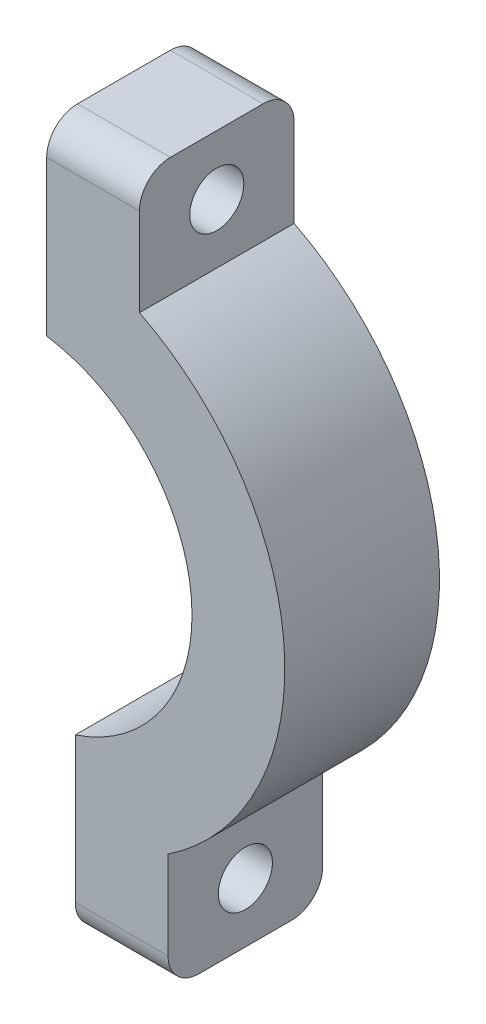
SolidWorks part; units mm, degrees
ref_plane "Front Plane" through (0, 0, 0) normal (0, 0, 1) x (1, 0, 0)
ref_plane "Top Plane" through (0, 0, 0) normal (0, 1, 0) x (1, 0, 0)
ref_plane "Right Plane" through (0, 0, 0) normal (1, 0, 0) x (0, 0, -1)
sketch "Sketch1" plane through (0, 0, 0) normal (0, 0, 1) x (1, 0, 0)
  line L2 (3.5, -17.05) -> (3.5, -10.4811)
  line L10 (3.5, -17.05) -> (3.5, -19.3581)
  line L13 (1.65, 20.4375) -> (1.65, 10.9261)
  line L16 (0, 0) -> (0, 22.7138) construction
  line L17 (7.65, 15.2375) -> (7.65, 22.9375)
  line L19 (7.65, 22.9375) -> (1.65, 22.9375)
  line L20 (1.65, 22.9375) -> (1.65, 20.4375)
  line L21 (9.5, -14.1581) -> (9.5, -21.8581)
  line L22 (9.5, -21.8581) -> (3.5, -21.8581)
  line L23 (3.5, -21.8581) -> (3.5, -19.3581)
  arc A0 (3.5, -10.4811) -> (1.65, 10.9261) centre (0, 0) ccw
  arc A1 (9.5, -14.1581) -> (7.65, 15.2375) centre (0, 0) ccw
  point P7 (0, -17.05)
  point P16 (0, 17.05)
extrude "Boss-Extrude1" add sketch "Sketch1" along normal blind 10 contours L2 A0 L13 L20 L19 L17 A1 L21 L22 L23 L10
sketch "Sketch2" plane through (7.65, 0, 0) normal (1, 0, 0) x (0, 0, -1)
  circle A0 centre (-5, 19.0875) radius 1.75
  dimension "D1" = 3.5
sketch "Sketch3" plane through (9.5, 0, 0) normal (1, 0, 0) x (0, 0, -1)
  circle A0 centre (-5, -18.0081) radius 1.75
  dimension "D1" = 3.5
extrude "Cut-Extrude1" cut sketch "Sketch3" against normal blind 10
extrude "Cut-Extrude2" cut sketch "Sketch2" against normal blind 10
fillet "Fillet1" radius 2 4 edges at (6.5, -21.8581, 10) (6.5, -21.8581, 0) (4.65, 22.9375, 0) (4.65, 22.9375, 10)
